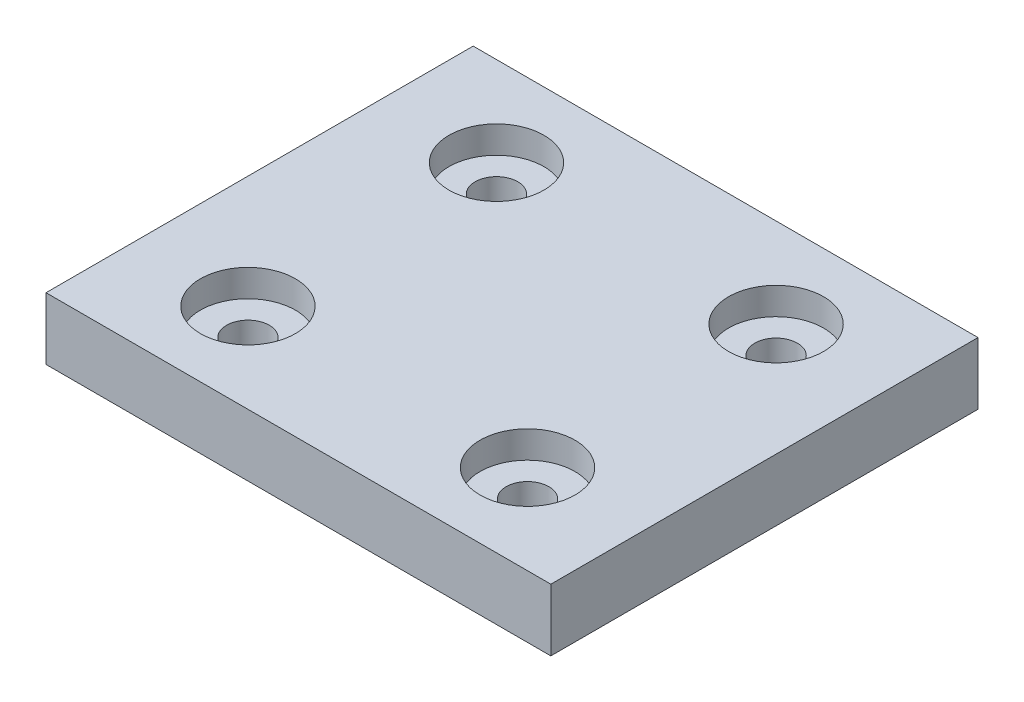
SolidWorks part; units mm, degrees
ref_plane "Front Plane" through (0, 0, 0) normal (0, 0, 1) x (1, 0, 0)
ref_plane "Top Plane" through (0, 0, 0) normal (0, 1, 0) x (1, 0, 0)
ref_plane "Right Plane" through (0, 0, 0) normal (1, 0, 0) x (0, 0, -1)
sketch "Sketch1" plane through (0, 0, 0) normal (0, 1, 0) x (1, 0, 0)
  line L1 (-32.5, 27.5) -> (32.5, 27.5)
  line L2 (-32.5, 27.5) -> (-32.5, -27.5)
  line L3 (-32.5, -27.5) -> (32.5, -27.5)
  line L4 (32.5, 27.5) -> (32.5, -27.5)
  line L5 (-32.5, 27.5) -> (32.5, -27.5) construction
  line L6 (-32.5, -27.5) -> (32.5, 27.5) construction
  point P0 (0, 0)
  dimension "D1" = 65
  dimension "D2" = 55
extrude "Boss-Extrude1" add sketch "Sketch1" along normal blind 8
hole_wizard "CBORE for M5 Hex Head Cap Screw1" positions "Sketch2" profile "Sketch3" counterbore size "M5" standard "ISO" end condition through all
sketch "Sketch2" plane through (0, 8, 0) normal (0, 1, 0) x (1, 0, 0)
  point P0 (-18, 16)
  point P2 (18, 16)
  point P4 (18, -16)
  point P6 (-18, -16)
  dimension "D1" = 36
  dimension "D2" = 32
  dimension "D3" = 16
  dimension "D4" = 18
sketch "Sketch3" plane through (-18, 8, -16) normal (1, 0, 0) x (0, 0, 1)
  line L0 (0, 0) -> (0, 8)
  line L1 (0, 8) -> (2.75, 8)
  line L3 (2.75, 8) -> (2.75, 3.5)
  line L4 (2.75, 3.5) -> (6.119, 3.5)
  line L5 (6.119, 3.5) -> (6.119, 0)
  line L7 (6.119, 0) -> (0, 0)
  line L11 (0, -6.35) -> (0, 107.95) construction
  dimension "Thru Hole Dia." = 5.5
  dimension "Thru Hole Depth" = 8
  dimension "C'Bore Dia." = 12.238
  dimension "C'Bore Depth" = 3.5
